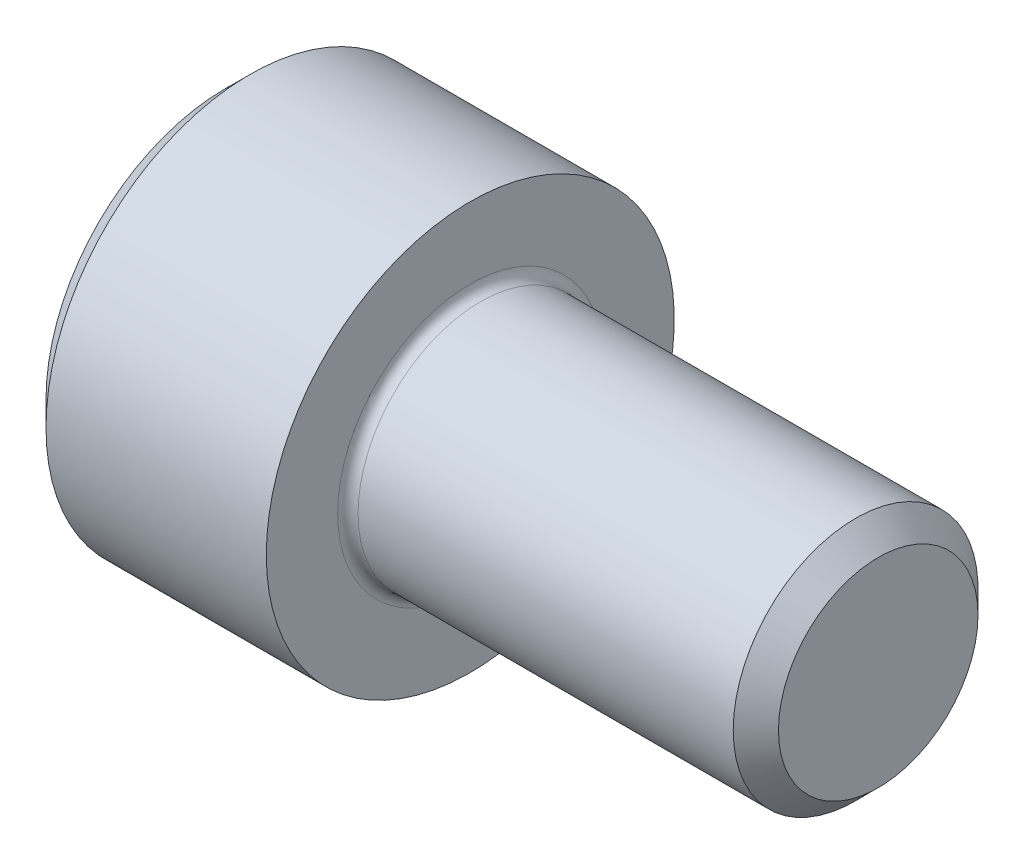
SolidWorks part; units mm, degrees
revolve "Base-Revolve" add sketch "BodySke"
sketch "BodySke" plane through (0, 0, 0) normal (0, 0, 1) x (1, 0, 0)
  line L0 (0, 0) -> (0, 4.4)
  line L1 (0.6, 5) -> (6, 5)
  line L2 (6, 5) -> (6, 3)
  line L3 (6, 3) -> (15.4455, 3)
  line L4 (16, 2.4455) -> (16, 0)
  line L5 (16, 0) -> (0, 0)
  line L6 (-31.75, 0) -> (127, 0) construction
  line L7 (0, 4.4) -> (0.6, 5)
  line L8 (16, 2.4455) -> (15.4455, 3)
  line L9 (0, -4.4) -> (0.6, -5) construction
  line L10 (16, -2.4455) -> (15.4455, -3) construction
  line L11 (7, 9.525) -> (7, 3.175) construction
  line L12 (6, 9.525) -> (6, 3.175) construction
  line L13 (-34, 9.525) -> (-34, 3.175) construction
  dimension "Diameter" = 6
  dimension "Head_ht" = 6
  dimension "Length" = 10
  dimension "Body_ch_ang" = 45
  dimension "Head_dia" = 10
  dimension "Head_ch_ang" = 45
  dimension "Minor_dia" = 4.891
  dimension "Advance" = 1
  dimension "Thread_nom" = 10
  dimension "Thread_length" = 50
  dimension "Head_ch_ht" = 0.6
cosmetic thread "ThreadCosmetic"
fillet "Fillet1" radius 0.25 1 edges at (6, 0, 3)
ref_plane "Plane1" through (0, 0, 0) normal (0, 0, 1) x (1, 0, 0)
ref_plane "Plane2" through (0, 0, 0) normal (0, 1, 0) x (1, 0, 0)
ref_plane "Plane3" through (0, 0, 0) normal (1, 0, 0) x (0, 0, -1)
sketch "Sketch2" plane through (0, 0, 0) normal (0, 0, 1) x (1, 0, 0)
  line L0 (0, 2.542) -> (3, 2.542)
  line L1 (3, 2.542) -> (4.4676, 0)
  line L2 (-31.75, 0) -> (127, 0) construction
  line L3 (4.4676, 0) -> (0, 0)
  line L4 (0, 0) -> (0, 2.542)
  line L5 (0, 4.4) -> (0, -4.4) construction
  line L6 (0, 0) -> (47.625, 0) construction
  line L7 (6, -5) -> (6, 5) construction
  dimension "D1" = 2.542
  dimension "D2" = 60
revolve "Hex-PreBroach" cut sketch "Sketch2" angle 360 about L6
sketch "Sketch3" plane through (0, 0, 0) normal (-1, 0, 0) x (0, 0.5, 0.866)
  line L0 (1.4676, 2.542) -> (-1.4676, 2.542)
  line L1 (-1.4676, 2.542) -> (-2.9352, 0)
  line L2 (1.4676, 2.542) -> (2.9352, 0)
  line L3 (1.4676, -2.542) -> (2.9352, 0)
  line L4 (1.4676, -2.542) -> (-1.4676, -2.542)
  line L5 (-1.4676, -2.542) -> (-2.9352, 0)
  dimension "D1" = 2.542
  dimension "D2" = 2.542
  dimension "Hex_size" = 5.084
extrude "Hex" cut sketch "Sketch3" against normal blind 3
sketch "Sketch4" plane through (0, 0, 0) normal (-1, 0, 0) x (0, 0, 1)
  line L0 (0, 0) -> (2.8067, 0)
  line L1 (0, 0) -> (6.1484, 3.5498) construction
  line L2 (0, 0) -> (1.4033, 2.4307)
  line L3 (2.3336, 0.614) -> (2.6851, 0.817)
  line L4 (1.6986, 1.7139) -> (2.0501, 1.9169)
  arc A0 (2.3336, 0.614) -> (1.6986, 1.7139) centre (0, 0) ccw
  arc A1 (2.8067, 0) -> (2.6851, 0.817) centre (0, 0) ccw
  arc A2 (1.4033, 2.4307) -> (2.0501, 1.9169) centre (0, 0) cw
  dimension "D1" = 30
  dimension "D2" = 60
  dimension "Spline_p_dim" = 1.27
  dimension "D3" = 0.635
extrude "Spline" [suppressed] cut sketch "Sketch4" against normal blind 3
pattern_circular "CirPattern1" [suppressed] count 6 every 60
sketch "Sketch5" plane through (0, 0, 0) normal (0, 0, 1) x (1, 0, 0)
  line L0 (-31.75, 0) -> (127, 0) construction
  line L2 (0, 4.4) -> (0, -4.4) construction
  circle A0 centre (2.3, 0) radius 0.675
  dimension "Drilled_hole_dia" = 1.35
  dimension "Drilled_hole_loc" = 2.3
extrude "Hole" [suppressed] cut sketch "Sketch5" against normal through all and the other way through all
pattern_circular "Drilled-4" [suppressed] count 2 every 60
pattern_circular "Drilled-6" [suppressed] count 3 every 60
sketch "ThdSchSke" plane through (0, 0, 0) normal (0, 0, 1) x (1, 0, 0)
  line L0 (7, -2.4455) -> (6.6117, -3)
  line L1 (7, -2.4455) -> (7.3883, -3)
  line L2 (7.3883, -3) -> (7.3883, -3.75)
  line L3 (-3.175, 0) -> (5.1513, 0) construction
  line L5 (7.3883, -3.75) -> (6.6117, -3.75)
  line L6 (6.6117, -3.75) -> (6.6117, -3)
  line L7 (0, 4.4) -> (0, -4.4) construction
  dimension "Thread_minor" = 4.891
  dimension "Diameter" = 6
  dimension "Start" = 7
revolve "ThreadSchematic" [suppressed] cut sketch "ThdSchSke" angle 360 about L3
pattern_linear "ThdSchPat" [suppressed]
equation "\"D2@Sketch3\" = \"Hex_size@Sketch3\" / 2"
equation "\"D1@Sketch3\" = \"Hex_size@Sketch3\" / 2"
equation "\"D1@Sketch2\" = \"Hex_size@Sketch3\" / 2"
equation "\"D3@Sketch4\" = \"Spline_p_dim@Sketch4\" / 2"
equation "\"Thread_minor@ThreadCosmetic\"  =  \"Minor_dia@BodySke\""
equation "\"D2@CirPattern1\" = 360 / \"Num_teeth@CirPattern1\""
equation "\"Wall_thickness@Sketch2\" = \"Head_ht@BodySke\" - \"Key_eng@Hex\""
equation "\"Thread_length@ThreadCosmetic\" = ((sgn( (\"Length@BodySke\" - \"Advance@BodySke\" ) - \"Thread_nom@BodySke\" )-1)*( (\"Length@BodySke\" - \"Advance@BodySke\" ) - \"Thread_nom@BodySke\" ))/-2+ \"Thread_nom@BodySke\""
equation "\"Thread_minor@ThdSchSke\" = \"Minor_dia@BodySke\""
equation "\"Diameter@ThdSchSke\" = \"Diameter@BodySke\""
equation "\"Overcut@ThdSchSke\" = \"Diameter@BodySke\" * 1.25"
equation "\"Start@ThdSchSke\" = \"Head_ht@BodySke\" + \"Length@BodySke\" - \"Thread_length@ThreadCosmetic\"  '---Non-countersunk---"
equation "\"Num_threads@ThdSchPat\" = int( \"Thread_length@ThreadCosmetic\" / \"Advance@BodySke\" + 0.999 )  + 1"
equation "\"Advance@ThdSchPat\" = \"Thread_length@ThreadCosmetic\" /  (\"Num_threads@ThdSchPat\" - 1) 'relax it"
equation "\"Num_threads@ThdSchPat\" = \"Num_threads@ThdSchPat\" - sgn( \"Num_threads@ThdSchPat\" - 1) '---chamfered tips only---"
